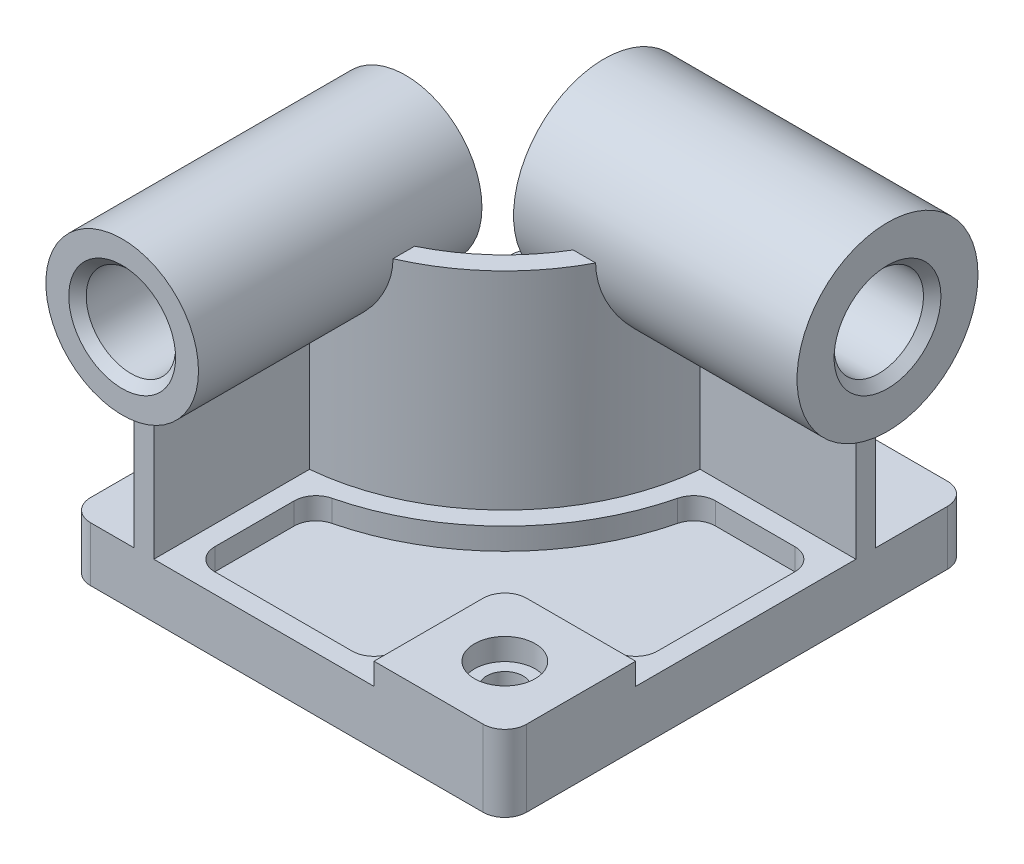
SolidWorks part; units mm, degrees
ref_plane "Front Plane" through (0, 0, 0) normal (0, 0, 1) x (1, 0, 0)
ref_plane "Top Plane" through (0, 0, 0) normal (0, 1, 0) x (1, 0, 0)
ref_plane "Right Plane" through (0, 0, 0) normal (1, 0, 0) x (0, 0, -1)
sketch "Sketch1" plane through (0, 0, 0) normal (0, 1, 0) x (1, 0, 0)
  line L1 (-100, 106.5) -> (100, 106.5)
  line L2 (-100, 106.5) -> (-100, -106.5)
  line L3 (-100, -106.5) -> (100, -106.5)
  line L4 (100, 106.5) -> (100, -106.5)
  line L5 (-100, 106.5) -> (100, -106.5) construction
  line L6 (-100, -106.5) -> (100, 106.5) construction
  point P0 (0, 0)
  dimension "D1" = 200
  dimension "D2" = 213
extrude "Boss-Extrude1" add sketch "Sketch1" along normal blind 25
fillet "Fillet1" radius 10 4 edges at (-100, 12.5, -106.5) (100, 12.5, -106.5) (100, 12.5, 106.5) (-100, 12.5, 106.5)
sketch "Sketch2" plane through (0, 25, 0) normal (0, 1, 0) x (1, 0, 0)
  line L1 (50, -46.5) -> (100, -46.5)
  line L2 (40, -56.5) -> (40, -106.5)
  line L3 (40, -106.5) -> (90, -106.5)
  line L4 (100, -46.5) -> (100, -96.5)
  line L5 (40, -46.5) -> (100, -106.5) construction
  line L6 (40, -106.5) -> (100, -46.5) construction
  arc A0 (90, -106.5) -> (100, -96.5) centre (90, -96.5) ccw
  arc A1 (40, -56.5) -> (50, -46.5) centre (50, -56.5) cw
  point P0 (70, -76.5)
  dimension "D3" = 10
  dimension "D4" = 10
  dimension "D1" = 60
  dimension "D2" = 60
extrude "Boss-Extrude2" add sketch "Sketch2" along normal blind 10
sketch "Sketch3" plane through (0, 25, 0) normal (0, 1, 0) x (1, 0, 0)
  line L0 (100, 63.5) -> (20, 63.5)
  line L1 (100, -46.5) -> (100, 96.5) construction
  line L2 (-70, -26.5) -> (-70, -106.5)
  line L3 (-90, -106.5) -> (40, -106.5) construction
  line L4 (100, -96.5) -> (100, -46.5) construction
  line L6 (100, 54.5) -> (28.5901, 54.5)
  line L7 (-61, -35.0901) -> (-61, -106.5)
  line L8 (100, 63.5) -> (100, 54.5)
  line L9 (-70, -106.5) -> (-61, -106.5)
  arc A0 (20, 63.5) -> (-70, -26.5) centre (-70, 63.5) cw
  arc A1 (28.5901, 54.5) -> (-61, -35.0901) centre (-70, 63.5) cw
  dimension "D1" = 80
  dimension "D2" = 80
  dimension "D3" = 170
  dimension "D4" = 9
extrude "Boss-Extrude3" add sketch "Sketch3" along normal blind 95
sketch "Sketch4" plane through (0, 0, 106.5) normal (0, 0, 1) x (1, 0, 0)
  line L0 (-70, 120) -> (-61, 120) construction
  circle A0 centre (-65.5, 120) radius 35
  dimension "D1" = 70
extrude "Boss-Extrude4" add sketch "Sketch4" along normal blind 10 and the other way blind 120 contours A0
sketch "Sketch6" plane through (0, 0, 116.5) normal (0, 0, 1) x (1, 0, 0)
  circle A0 centre (-65.5, 120) radius 20.5
  dimension "D1" = 41
extrude "Cut-Extrude1" cut sketch "Sketch6" against normal through all both and the other way through all
sketch "Sketch7" plane through (100, 0, 0) normal (1, 0, 0) x (0, 0, -1)
  line L0 (54.5, 120) -> (63.5, 120) construction
  circle A0 centre (59, 120) radius 41.5
  dimension "D1" = 83
extrude "Boss-Extrude5" add sketch "Sketch7" along normal blind 10 and the other way blind 120
sketch "Sketch8" plane through (110, 0, 0) normal (1, 0, 0) x (0, 0, -1)
  circle A0 centre (59, 120) radius 20.5
  dimension "D1" = 41
extrude "Cut-Extrude2" cut sketch "Sketch8" against normal through all both and the other way through all
chamfer "Chamfer1" distance 4 angle 45 4 edges at (-20, 120, -79.5) (110, 120, -79.5) (-45, 120, -13.5) (-45, 120, 116.5)
sketch "Sketch9" plane through (0, 25, 0) normal (0, 1, 0) x (1, 0, 0)
  line L0 (81, 45.5) -> (44.6298, 45.5)
  line L1 (91, -27.5) -> (91, 35.5)
  line L2 (50, -37.5) -> (81, -37.5)
  line L3 (31, -87.5) -> (31, -56.5)
  line L4 (-42, -97.5) -> (21, -97.5)
  line L5 (-52, -51.1298) -> (-52, -87.5)
  line L6 (-61, -35.0901) -> (-61, -106.5)
  line L7 (-61, -106.5) -> (40, -106.5)
  line L8 (40, -106.5) -> (40, -56.5)
  line L9 (50, -46.5) -> (100, -46.5)
  line L10 (100, -46.5) -> (100, 54.5)
  line L11 (100, 54.5) -> (28.5901, 54.5)
  line L14 (40, -106.5) -> (40, -56.5)
  line L15 (50, -46.5) -> (100, -46.5)
  line L18 (91, 45.5) -> (36.4894, 45.5) construction
  line L19 (91, -37.5) -> (91, 45.5) construction
  line L20 (50, -37.5) -> (91, -37.5) construction
  line L21 (31, -97.5) -> (31, -56.5) construction
  line L22 (-52, -97.5) -> (31, -97.5) construction
  line L23 (-52, -42.9894) -> (-52, -97.5) construction
  line L24 (-61, -35.0901) -> (-61, -106.5) construction
  line L25 (-61, -106.5) -> (40, -106.5) construction
  line L26 (100, -46.5) -> (100, 54.5) construction
  line L27 (100, 54.5) -> (28.5901, 54.5) construction
  arc A0 (-44.3729, -41.4154) -> (34.9154, 37.8729) centre (-70, 63.5) ccw
  arc A1 (50, -37.5) -> (31, -56.5) centre (50, -56.5) ccw
  arc A2 (-61, -35.0901) -> (28.5901, 54.5) centre (-70, 63.5) ccw
  arc A3 (50, -46.5) -> (40, -56.5) centre (50, -56.5) ccw
  arc A5 (50, -46.5) -> (40, -56.5) centre (50, -56.5) ccw
  arc A6 (-52, -42.9894) -> (36.4894, 45.5) centre (-70, 63.5) ccw construction
  arc A7 (34.9154, 37.8729) -> (44.6298, 45.5) centre (44.6298, 35.5) cw
  arc A8 (81, 45.5) -> (91, 35.5) centre (81, 35.5) cw
  arc A9 (91, -27.5) -> (81, -37.5) centre (81, -27.5) cw
  arc A10 (31, -87.5) -> (21, -97.5) centre (21, -87.5) cw
  arc A11 (-42, -97.5) -> (-52, -87.5) centre (-42, -87.5) cw
  arc A12 (-52, -51.1298) -> (-44.3729, -41.4154) centre (-42, -51.1298) cw
  arc A13 (-61, -35.0901) -> (28.5901, 54.5) centre (-70, 63.5) ccw construction
  dimension "D3" = 10
  dimension "D1" = 0
  dimension "D2" = 9
extrude "Cut-Extrude3" cut sketch "Sketch9" against normal blind 10 contours L1 A8 L0 A7 A0 A12 L5 A11 L4 A10 L3 A1 L2 A9
sketch "Sketch10" plane through (0, 35, 0) normal (0, 1, 0) x (1, 0, 0)
  line L0 (100, -96.5) -> (100, -46.5) construction
  line L2 (40, -106.5) -> (90, -106.5) construction
  circle A0 centre (70, -76.5) radius 13.9202
  point P6 (71.3094, -106.5)
  dimension "D1" = 30
  dimension "D2" = 30
extrude "Cut-Extrude4" cut sketch "Sketch10" against normal blind 10
sketch "Sketch11" plane through (0, 25, 0) normal (0, 1, 0) x (1, 0, 0)
  circle A0 centre (70, -76.5) radius 8.3574
extrude "Cut-Extrude5" cut sketch "Sketch11" against normal through all
